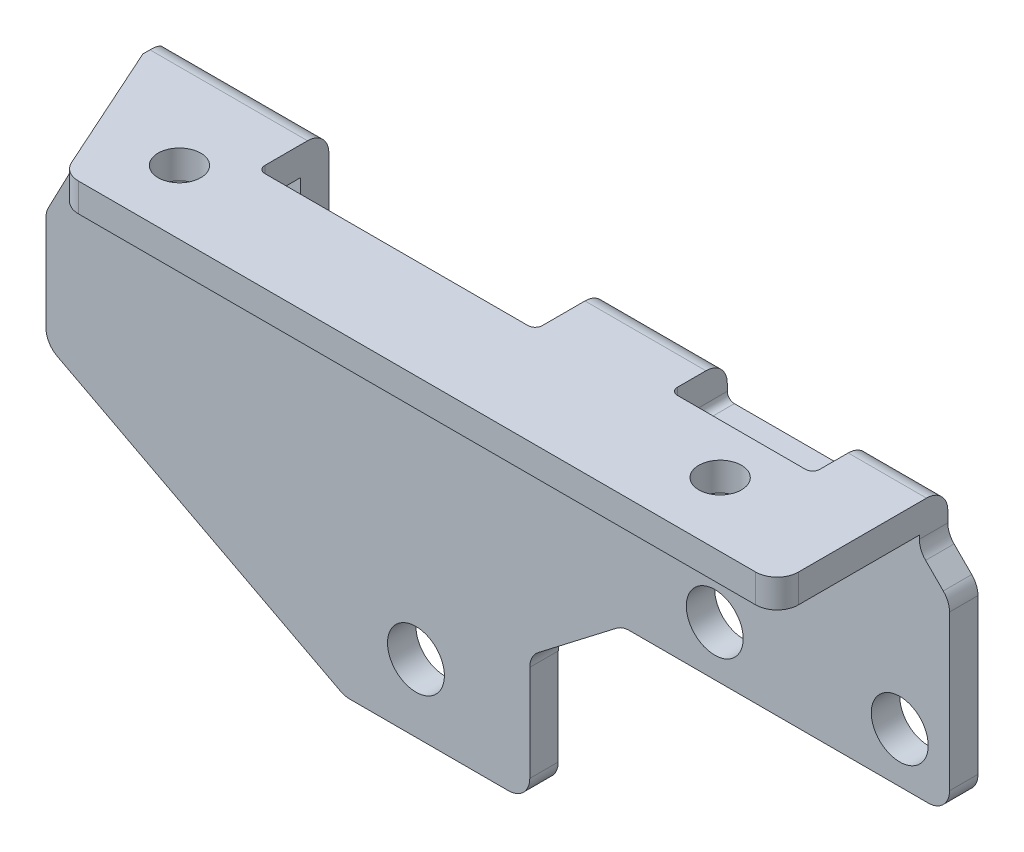
SolidWorks part; units mm, degrees
material "1060 Alloy"
ref_plane "Front Plane" through (0, 0, 0) normal (0, 0, 1) x (1, 0, 0)
ref_plane "Top Plane" through (0, 0, 0) normal (0, 1, 0) x (1, 0, 0)
ref_plane "Right Plane" through (0, 0, 0) normal (1, 0, 0) x (0, 0, -1)
sketch "Sketch1" plane through (0, 0, 0) normal (0, 0, 1) x (1, 0, 0)
  line L0 (0, 0) -> (21, -11)
  line L1 (21, -11) -> (27.7289, -11)
  line L2 (0, 0) -> (0, 8)
  line L3 (0, 8) -> (6.8095, 21)
  line L7 (63.5, 16) -> (63.5, 3)
  line L8 (63.5, 3) -> (40.5, 3)
  line L9 (40.5, 3) -> (34, -2)
  line L10 (34, -2) -> (34, -11)
  line L11 (34, -11) -> (27.7289, -11)
  line L12 (63.5, 16) -> (61.3787, 18.1213)
  line L13 (61.3787, 18.1213) -> (61.3787, 21)
  line L14 (61.3787, 21) -> (6.8095, 21)
  circle A0 centre (26, -6.25) radius 2
  circle A1 centre (47, 6.5) radius 2
  circle A2 centre (60, 6.5) radius 2
  circle A3 centre (7.5, 16) radius 2
  dimension "D12" = 4
  dimension "D13" = 4.75
  dimension "D14" = 8
  dimension "D15" = 4
  dimension "D16" = 3.5
  dimension "D17" = 3.5
  dimension "D18" = 13
  dimension "D19" = 4
  dimension "D20" = 7.5
  dimension "D21" = 27
  dimension "D1" = 13
  dimension "D2" = 9
  dimension "D3" = 21
  dimension "D4" = 11
  dimension "D5" = 8
  dimension "D6" = 13
  dimension "D7" = 5
  dimension "D8" = 6.5
  dimension "D9" = 23
  dimension "D10" = 13
  dimension "D11" = 3
extrude "Boss-Extrude1" add sketch "Sketch1" along normal blind 2
sketch "Sketch2" plane through (0, 0, 2) normal (0, 0, 1) x (1, 0, 0)
  line L1 (61.3787, 21) -> (6.8095, 21)
  line L2 (61.3787, 21) -> (61.3787, 19)
  line L3 (61.3787, 19) -> (6.8095, 19)
  line L4 (6.8095, 21) -> (6.8095, 19)
  dimension "D1" = 2
extrude "Boss-Extrude2" add sketch "Sketch2" along normal blind 10
sketch "Sketch3" plane through (0, 21, 0) normal (0, 1, 0) x (1, 0, 0)
  line L0 (6.8095, -2) -> (11.3095, -12)
  line L1 (61.3787, -12) -> (6.8095, -12) construction
  line L2 (11.3095, -12) -> (6.8095, -12)
  line L3 (6.8095, -12) -> (6.8095, -2)
  line L4 (61.3787, -12) -> (61.3787, 0) construction
  circle A0 centre (52.8787, -7.5) radius 1.5
  circle A1 centre (14.8787, -7.5) radius 1.5
  point P11 (0, 0)
  dimension "D2" = 3
  dimension "D3" = 8.5
  dimension "D4" = 4.5
  dimension "D5" = 38
  dimension "D1" = 4.5
extrude "Cut-Extrude1" cut sketch "Sketch3" against normal through all
sketch "Sketch4" plane through (0, 21, 0) normal (0, 1, 0) x (1, 0, 0)
  line L0 (61.3787, 0) -> (6.8095, 0) construction
  line L1 (17.8787, 0) -> (37.3787, 0)
  line L2 (17.8787, 0) -> (17.8787, -5)
  line L3 (17.8787, -5) -> (37.3787, -5)
  line L4 (37.3787, 0) -> (37.3787, -5)
  line L5 (61.3787, -12) -> (61.3787, 0) construction
  line L6 (55.8787, 0) -> (45.8787, 0)
  line L7 (55.8787, 0) -> (55.8787, -4)
  line L8 (55.8787, -4) -> (45.8787, -4)
  line L9 (45.8787, 0) -> (45.8787, -4)
  line L10 (61.3787, -12) -> (11.3095, -12) construction
  dimension "D1" = 5.5
  dimension "D2" = 8
  dimension "D3" = 10
  dimension "D4" = 7
  dimension "D5" = 8.5
  dimension "D6" = 19.5
extrude "Cut-Extrude2" cut sketch "Sketch4" against normal offset from surface (2.5 mm away) 15.5 up to face at (52, 3, 1)
sketch "Sketch5" plane through (0, 18.5, 0) normal (0, 1, 0) x (1, 0, 0)
  line L1 (17.8787, 0) -> (37.3787, 0)
  line L2 (17.8787, 0) -> (17.8787, -2)
  line L3 (17.8787, -2) -> (37.3787, -2)
  line L4 (37.3787, 0) -> (37.3787, -2)
extrude "Cut-Extrude3" cut sketch "Sketch5" against normal offset from surface (4.5 mm away) 25 up to face at (27.5, -11, 1)
fillet "Fillet1" radius 1.5 14 edges at (61.3787, 20, 12) (11.3095, 20, 12) (0, 8, 1) (0, 0, 1) (21, -11, 1) (34, -11, 1) (34, -2, 1) (40.5, 3, 1) (63.5, 3, 1) (61.3787, 18.1213, 1) (63.5, 16, 1) (12.3441, 21, 0) (41.6287, 21, 0) (58.6287, 21, 0)
fillet "Fillet2" radius 0.5 8 edges at (37.3787, 20, 5) (37.3787, 14, 1) (55.8787, 20, 4) (45.8787, 20, 4) (45.8787, 18.5, 1) (55.8787, 18.5, 1) (17.8787, 14, 1) (17.8787, 20, 5)
